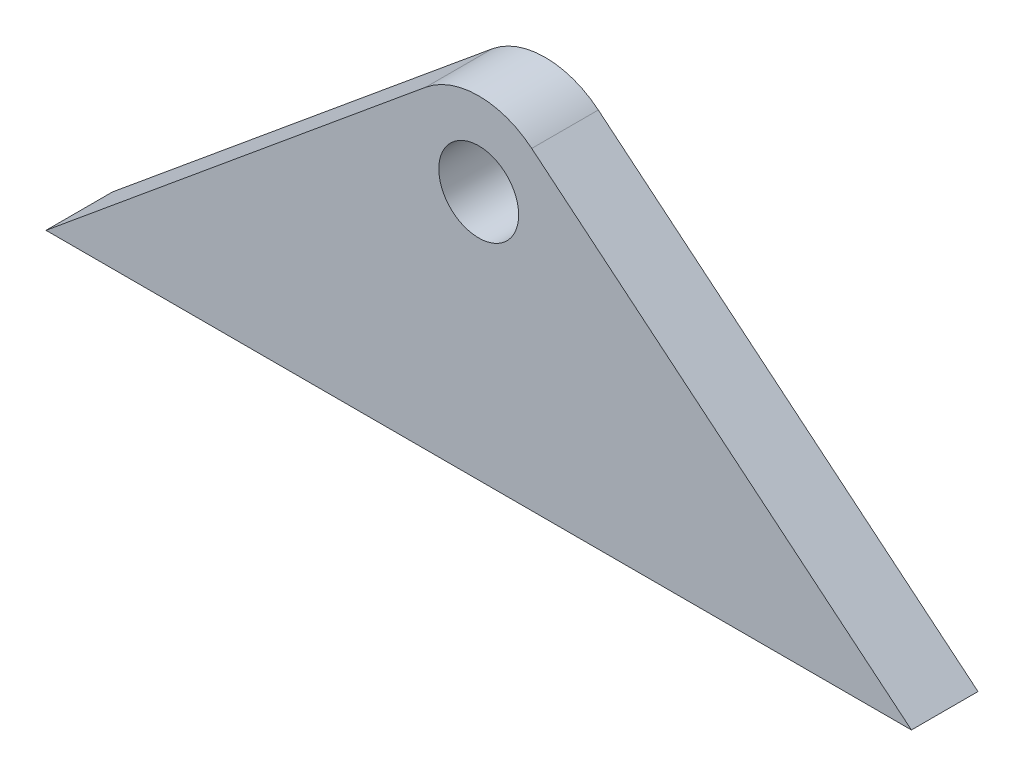
SolidWorks part; units mm, degrees
ref_plane "Front Plane" through (0, 0, 0) normal (0, 0, 1) x (1, 0, 0)
ref_plane "Top Plane" through (0, 0, 0) normal (0, 1, 0) x (1, 0, 0)
ref_plane "Right Plane" through (0, 0, 0) normal (1, 0, 0) x (0, 0, -1)
sketch "Sketch2" plane through (0, 0, 0) normal (0, 0, 1) x (1, 0, 0)
  line L0 (0, 0) -> (0, 75)
  line L1 (130, 0) -> (-130, 0)
  line L2 (-130, 0) -> (-15.9256, 94.2711)
  line L3 (130, 0) -> (15.9256, 94.2711)
  arc A0 (15.9256, 94.2711) -> (-15.9256, 94.2711) centre (0, 75) ccw
  circle A1 centre (0, 75) radius 12
  dimension "D3" = 25
  dimension "D4" = 24
  dimension "D1" = 260
  dimension "D2" = 75
extrude "Boss-Extrude1" add sketch "Sketch2" along normal mid plane 20
